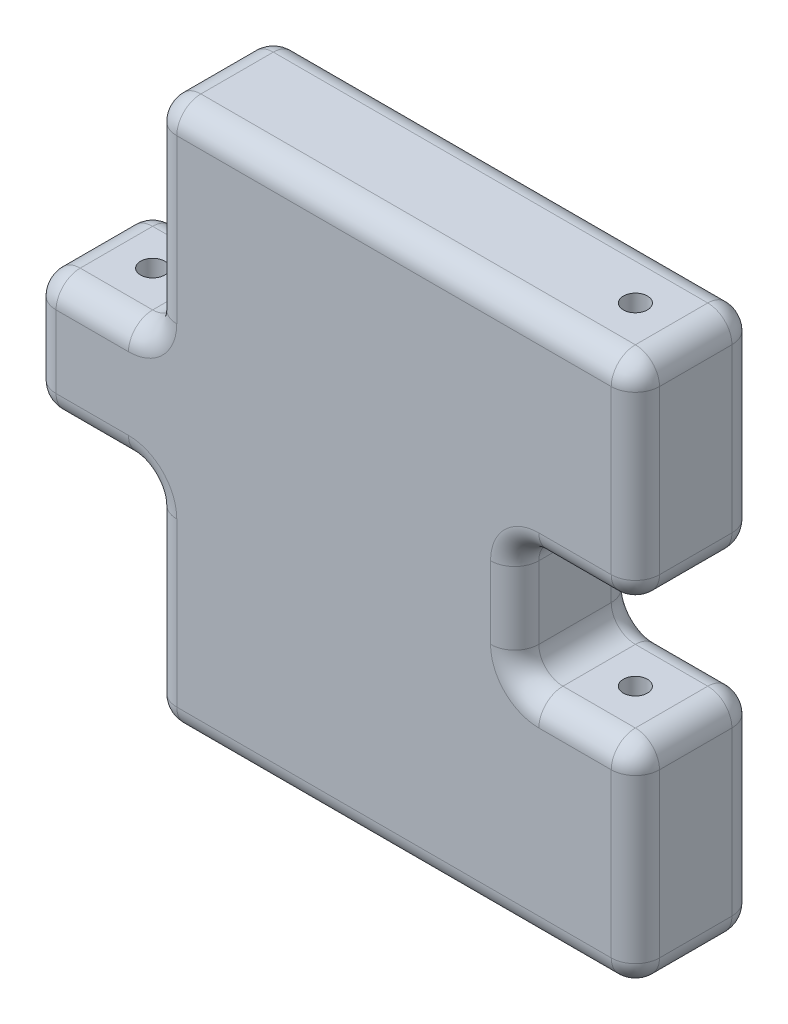
SolidWorks part; units mm, degrees
ref_plane "Front Plane" through (0, 0, 0) normal (0, 0, 1) x (1, 0, 0)
ref_plane "Top Plane" through (0, 0, 0) normal (0, 1, 0) x (1, 0, 0)
ref_plane "Right Plane" through (0, 0, 0) normal (1, 0, 0) x (0, 0, -1)
sketch "Sketch1" plane through (0, 0, 0) normal (0, 0, 1) x (1, 0, 0)
  line L0 (0, 0) -> (76.608, 0) construction
  line L1 (0, 0) -> (0, 43.3215) construction
  line L2 (10, 22.5) -> (-30, 22.5)
  line L3 (-30, 22.5) -> (-30, 5)
  line L4 (-30, -22.5) -> (10, -22.5)
  line L5 (10, -22.5) -> (10, -5)
  line L6 (10, -5) -> (0, -5)
  line L7 (0, -5) -> (0, 5)
  line L8 (0, 5) -> (10, 5)
  line L9 (10, 5) -> (10, 22.5)
  line L10 (-30, 5) -> (-40, 5)
  line L11 (-40, 5) -> (-40, -5)
  line L12 (-40, -5) -> (-30, -5)
  line L13 (-30, -5) -> (-30, -22.5)
  dimension "D1" = 45
  dimension "D2" = 40
  dimension "D3" = 10
extrude "Boss-Extrude1" add sketch "Sketch1" along normal blind 10
fillet "Fillet1" radius 2 36 edges at (10, 13.75, 10) (5, 5, 10) (10, 5, 5) (5, -5, 10) (10, -13.75, 10) (10, -5, 5) (0, -5, 5) (0, 0, 10) (0, 5, 5) (10, 22.5, 5) (-10, 22.5, 10) (-40, 0, 10) (-35, 5, 10) (-40, 5, 5) (-30, 22.5, 5) (-30, 13.75, 10) (-30, 5, 5) (-40, -5, 5) (-35, -5, 10) (-30, -5, 5) (-30, -13.75, 10) (-30, -22.5, 5) (-10, -22.5, 10) (10, -22.5, 5) (-40, 0, 0) (-35, -5, 0) (-30, -13.75, 0) (-10, -22.5, 0) (10, -13.75, 0) (5, -5, 0) (0, 0, 0) (5, 5, 0) (10, 13.75, 0) (-10, 22.5, 0) (-30, 13.75, 0) (-35, 5, 0)
sketch "Sketch2" plane through (0, 5, 0) normal (0, -1, 0) x (1, 0, 0)
  line L0 (8, 5) -> (-40, 5) construction
  line L1 (8, 2) -> (8, 8) construction
  line L2 (-40, 2) -> (-40, 8) construction
  line L3 (5, 8) -> (5, 2) construction
  line L4 (8, 8) -> (2, 8) construction
  line L5 (-28, 2) -> (8, 2) construction
  line L6 (-35, 8) -> (-35, 2) construction
  line L7 (-32, 8) -> (-38, 8) construction
  line L8 (-38, 2) -> (-32, 2) construction
  circle A0 centre (5, 5) radius 1
  circle A1 centre (-35, 5) radius 1
  dimension "D1" = 2
  dimension "D2" = 2
extrude "Cut-Extrude1" cut sketch "Sketch2" against normal through all both and the other way through all contours A1 | A0
